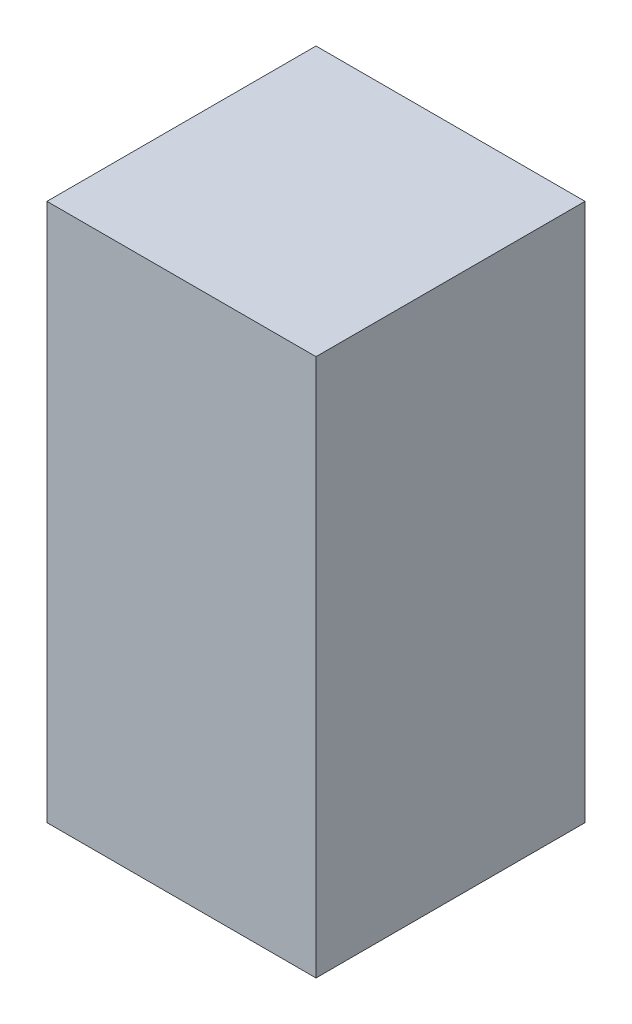
SolidWorks part; units mm, degrees
ref_plane "前视基准面" through (0, 0, 0) normal (0, 0, 1) x (1, 0, 0)
ref_plane "上视基准面" through (0, 0, 0) normal (0, 1, 0) x (1, 0, 0)
ref_plane "右视基准面" through (0, 0, 0) normal (1, 0, 0) x (0, 0, -1)
other "Configuration Table"
sketch "草图1" plane through (0, 0, 0) normal (0, 1, 0) x (1, 0, 0)
  line L1 (-10, 10) -> (10, 10)
  line L2 (-10, 10) -> (-10, -10)
  line L3 (-10, -10) -> (10, -10)
  line L4 (10, 10) -> (10, -10)
  line L5 (-10, 10) -> (10, -10) construction
  line L6 (-10, -10) -> (10, 10) construction
  point P0 (0, 0)
  dimension "D1" = 20
  dimension "D2" = 20
extrude "凸台-拉伸1" add sketch "草图1" along normal blind 40
